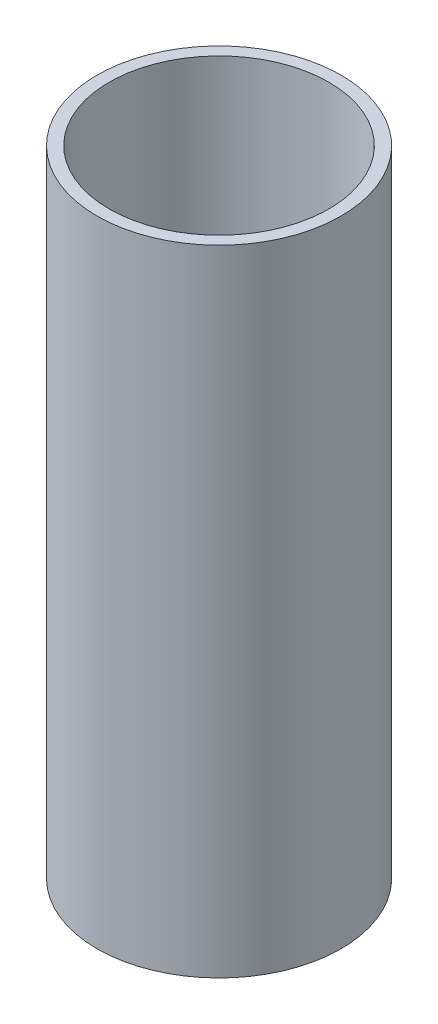
SolidWorks part; units mm, degrees
ref_plane "Front Plane" through (0, 0, 0) normal (0, 0, 1) x (1, 0, 0)
ref_plane "Top Plane" through (0, 0, 0) normal (0, 1, 0) x (1, 0, 0)
ref_plane "Right Plane" through (0, 0, 0) normal (1, 0, 0) x (0, 0, -1)
sketch "Sketch1" plane through (0, 0, 0) normal (0, 1, 0) x (1, 0, 0)
  circle A0 centre (0, 0) radius 25
  circle A1 centre (0, 0) radius 22.5
  dimension "D1" = 50
  dimension "D2" = 45
extrude "Boss-Extrude2" add sketch "Sketch1" along normal blind 130
equation "\"shaft_diameter\"= 50mm"
equation "\"shaft_radius\"= \"shaft_diameter\" / 2"
equation "\"D1@Sketch1\"=\"shaft_diameter\""
equation "\"shaft_inner_diameter\" = \"shaft_diameter\" - 2 * ( \"shaft_wall_thickness\" )"
equation "\"shaft_wall_thickness\"= 2.5"
equation "\"D2@Sketch1\"=\"shaft_inner_diameter\""
